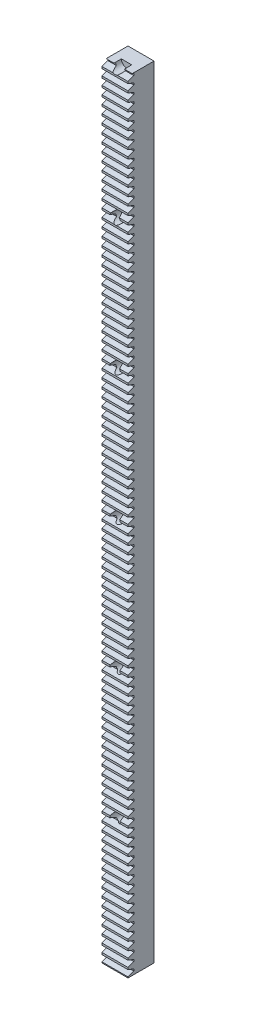
SolidWorks part; units mm, degrees
material "聚脂树脂"
ref_plane "前视基准面" through (0, 0, 0) normal (0, 0, 1) x (1, 0, 0)
ref_plane "上视基准面" through (0, 0, 0) normal (0, 1, 0) x (1, 0, 0)
ref_plane "右视基准面" through (0, 0, 0) normal (1, 0, 0) x (0, 0, -1)
other "Configuration Table"
sketch "草图3" plane through (0, 0, 0) normal (0, 1, 0) x (1, 0, 0)
  line L1 (0, 0) -> (20, 0)
  line L2 (0, 0) -> (0, 20)
  line L3 (0, 20) -> (20, 20)
  line L4 (20, 0) -> (20, 20)
  dimension "D1" = 20
  dimension "D2" = 20
extrude "凸台-拉伸1" add sketch "草图3" along normal blind 600
sketch "草图4" plane through (0, 0, 0) normal (1, 0, 0) x (0, 0, -1)
  line L0 (-36.1119, 0) -> (48.2922, 0) construction
  line L1 (0, 0) -> (0, 0.7486)
  line L2 (0, 600) -> (0, 0) construction
  line L3 (0, 0.7486) -> (4.5, 2.3864)
  line L4 (4.5, 2.3864) -> (4.5, 3.8836)
  line L5 (4.5, 3.8836) -> (0, 5.5214)
  line L6 (0, 5.5214) -> (0, 6.27)
  line L7 (-6.5746, 3.135) -> (9.1145, 3.135) construction
  line L8 (2.25, 5.2351) -> (2.25, 0.4412) construction
  line L9 (0, 6.27) -> (-2, 6.27)
  line L10 (-2, 6.27) -> (-2, 0)
  line L11 (-2, 0) -> (0, 0)
  point P14 (2.25, 4.7025)
  point P15 (2.25, 1.5675)
  dimension "D1" = 6.27
  dimension "D2" = 4.5
  dimension "D3" = 2.25
  dimension "D4" = 3.135
  dimension "D5" = 20
  dimension "D6" = 2
extrude "切除-拉伸1" cut sketch "草图4" along normal up to next
pattern_linear "阵列(线性)1" count 96 spacing 6.27 along (0, 1, 0) of "切除-拉伸1"
sketch "草图5" plane through (0, 0, 0) normal (0, 1, 0) x (1, 0, 0)
  circle A0 centre (10, 10) radius 4
  dimension "D3" = 8
  dimension "D1" = 10
  dimension "D2" = 10
extrude "切除-拉伸2" cut sketch "草图5" along normal blind 20
sketch "草图6" plane through (0, 0, 0) normal (0, 0, 1) x (1, 0, 0)
  line L0 (10, -11.5623) -> (10, 414.8088) construction
  line L1 (10, 100) -> (10, 200) construction
  circle A0 centre (10, 100) radius 2
  circle A1 centre (10, 200) radius 2
  circle A2 centre (10, 300) radius 2
  circle A3 centre (10, 400) radius 2
  circle A4 centre (10, 500) radius 2
  dimension "D2" = 4
  dimension "D1" = 10
  dimension "D3" = 100
  dimension "D5" = 100
  dimension "D4" = 5
extrude "切除-拉伸3" cut sketch "草图6" against normal through all
sketch "草图7" plane through (0, 0, 0) normal (0, 0, 1) x (1, 0, 0)
  line L0 (10, 100) -> (10, 200) construction
  circle A0 centre (10, 100) radius 4
  circle A1 centre (10, 200) radius 4
  circle A2 centre (10, 300) radius 4
  circle A3 centre (10, 400) radius 4
  circle A4 centre (10, 500) radius 4
  circle A5 centre (10, 600) radius 4
  point P0 (10, 100)
  dimension "D1" = 8
  dimension "D3" = 100
  dimension "D2" = 6
extrude "切除-拉伸4" cut sketch "草图7" against normal blind 8.9
